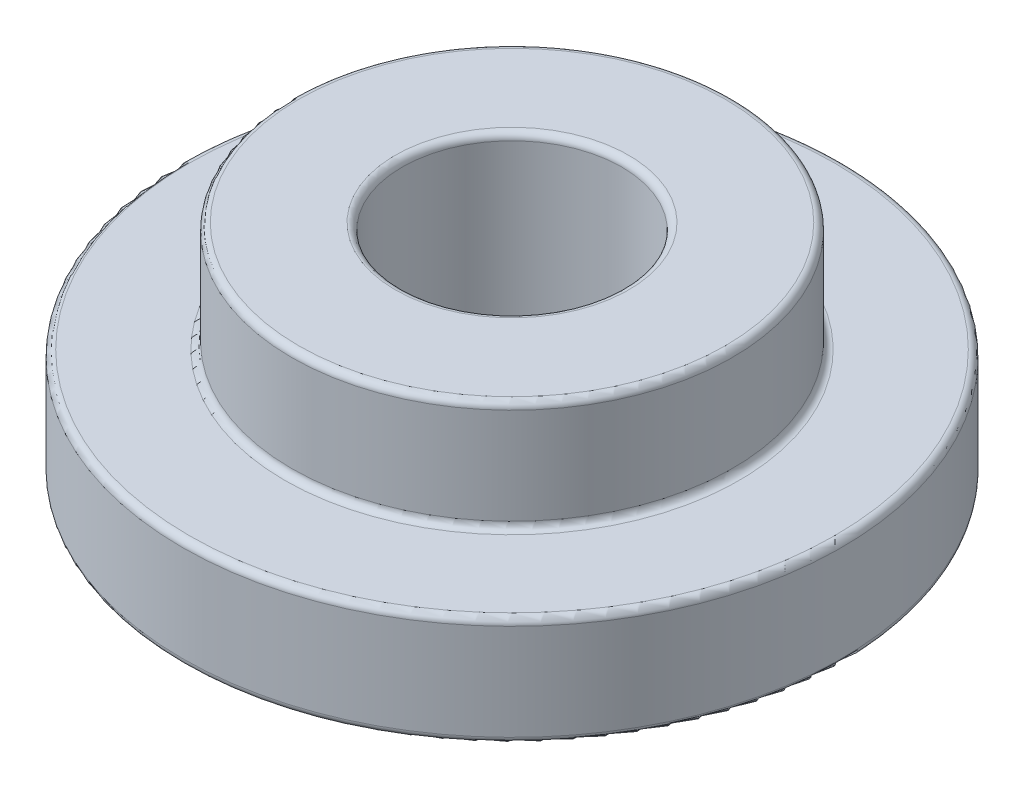
SolidWorks part; units mm, degrees
ref_plane "Front" through (0, 0, 0) normal (0, 0, 1) x (1, 0, 0)
ref_plane "Top" through (0, 0, 0) normal (0, 1, 0) x (1, 0, 0)
ref_plane "Right" through (0, 0, 0) normal (1, 0, 0) x (0, 0, -1)
sketch "Sketch1" plane through (0, 0, 0) normal (0, 1, 0) x (1, 0, 0)
  circle A0 centre (0, 0) radius 2
  circle A1 centre (0, 0) radius 4.01
  circle A2 centre (0, 0) radius 6
  dimension "ID" = 4
  dimension "OD" = 8.02
  dimension "FlangeOD" = 12
sketch "Sketch2" plane through (0, 0, 0) normal (1, 0, 0) x (0, 0, -1)
  line L0 (6, 0) -> (6, 2) construction
  line L1 (-4.01, 0) -> (-4.01, 4) construction
  line L8 (0, 0) -> (0, 4) construction
  point P5 (-6, 0)
  dimension "Flange Thickness" = 2
  dimension "Length" = 4
sketch "Sketch3" plane through (0, 0, 0) normal (0, 1, 0) x (1, 0, 0)
  circle A0 centre (0, 0) radius 2 construction
  circle A1 centre (0, 0) radius 4.01 construction
  circle A2 centre (0, 0) radius 2
  circle A3 centre (0, 0) radius 4.01
extrude "Boss-Extrude1" add sketch "Sketch3" along normal up to vertex (4 mm away) up to point (0, 4, 4.01)
sketch "Sketch4" plane through (0, 0, 0) normal (0, 1, 0) x (1, 0, 0)
  circle A0 centre (0, 0) radius 6 construction
  circle A1 centre (0, 0) radius 4.01 construction
  circle A2 centre (0, 0) radius 6
  circle A3 centre (0, 0) radius 4.01
extrude "Boss-Extrude2" add sketch "Sketch4" along normal up to vertex (2 mm away) up to point (0, 2, -6)
fillet "Fillet1" radius 0.125 6 edges at (0, 0, 2) (0, 0, 6) (0, 2, 4.01) (0, 2, 6) (0, 4, 2) (0, 4, 4.01)
